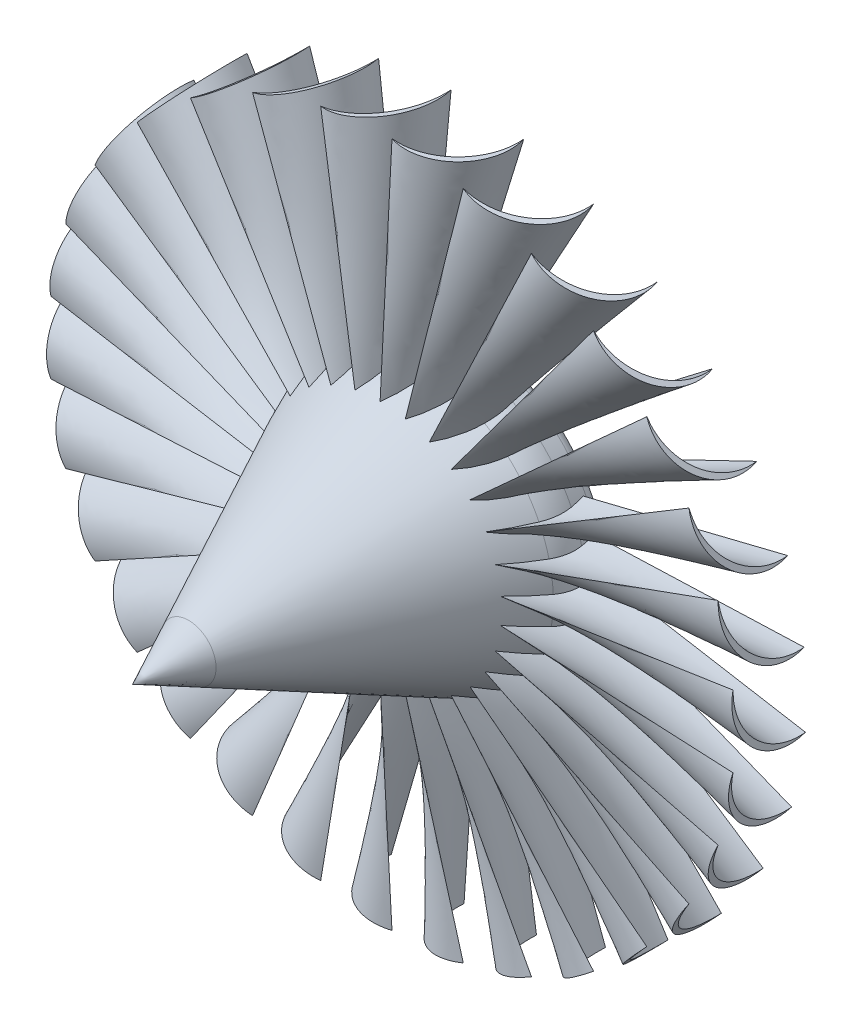
SolidWorks part; units mm, degrees
ref_plane "Front Plane" through (0, 0, 0) normal (0, 0, 1) x (1, 0, 0)
ref_plane "Top Plane" through (0, 0, 0) normal (0, 1, 0) x (1, 0, 0)
ref_plane "Right Plane" through (0, 0, 0) normal (1, 0, 0) x (0, 0, -1)
ref_plane "Plane1" through (0, 60, 0) normal (0, 1, 0) x (1, 0, 0)
ref_plane "Plane2" through (0, 170, 0) normal (0, 1, 0) x (1, 0, 0)
sketch "Sketch2" plane through (0, 60, 0) normal (0, 1, 0) x (1, 0, 0)
  arc A0 (0, 122.7) -> (0, 159.6) centre (-57.8831, 141.15) ccw
  arc A1 (0, 159.6) -> (0, 122.7) centre (-26.0638, 141.15) cw
  point P5 (2.8693, 141.15)
  point P6 (5.8693, 141.15)
  dimension "D3" = 3
  dimension "D1" = 122.7
  dimension "D2" = 36.9
sketch "Sketch3" plane through (0, 170, 0) normal (0, 1, 0) x (1, 0, 0)
  arc A0 (0, 128.6) -> (32.85, 161.1) centre (3.2417, 158.1753) ccw
  arc A1 (0, 128.6) -> (32.85, 161.1) centre (7.9491, 153.4172) ccw
  point P3 (24.1668, 137.0248)
  point P6 (26.2768, 134.8921)
  dimension "D1" = 128.6
  dimension "D2" = 32.85
  dimension "D3" = 32.5
  dimension "D4" = 3
sketch3d "3DSketch2"
  spline S0 degree 2 poles (32.85, 170, -161.1) (52.6601, 102.6613, -175.1482) (0, 60, -159.6) knots 0 0 0 1 1 1
  spline S1 degree 2 poles (0, 170, -128.6) (0, 115.4238, -112.5495) (0, 60, -122.7) knots 0 0 0 1 1 1
  point P5 (0, 0, 0)
  point P9 (32.9972, 104.1497, -167.63)
loft "Loft2" add profiles "Sketch2", "Sketch3"
sketch "Sketch4" plane through (0, 0, 0) normal (1, 0, 0) x (0, 0, -1)
  line L0 (0, 0) -> (166, 0)
  line L1 (166, 0) -> (166, 71.5534)
  line L2 (166, 71.5534) -> (153.2689, 71.5534)
  line L3 (140.0903, 68.5038) -> (0, 0)
  arc A0 (153.2689, 71.5534) -> (140.0903, 68.5038) centre (153.2689, 41.5534) ccw
  dimension "D2" = 30
  dimension "D1" = 166
revolve "Revolve1" add sketch "Sketch4" angle 360 about L0
ref_axis "Axis1" through (0, 0, -280.1805) along (0, 0, 1)
pattern_circular "CirPattern1" count 30 over 360 about axis through (0, 0, -280.1805) along (0, 0, 1) of "Loft2"
sketch "Sketch5" plane through (0, 0, 0) normal (1, 0, 0) x (0, 0, -1)
  line L0 (27.7786, -76.3086) -> (27.7786, 76.3086)
  point P3 (27.7786, 0)
split line "Split Line1"
sketch "Sketch6" plane through (0, 0, -166) normal (0, 0, -1) x (-1, 0, 0)
  circle A0 centre (0, 0) radius 20
  dimension "D1" = 40
extrude "Cut-Extrude1" cut sketch "Sketch6" against normal blind 38
fillet "Fillet1" radius 5 1 edges at (71.5534, 0, -166)
fillet "Fillet2" radius 5 1 edges at (-20, 0, -166)
